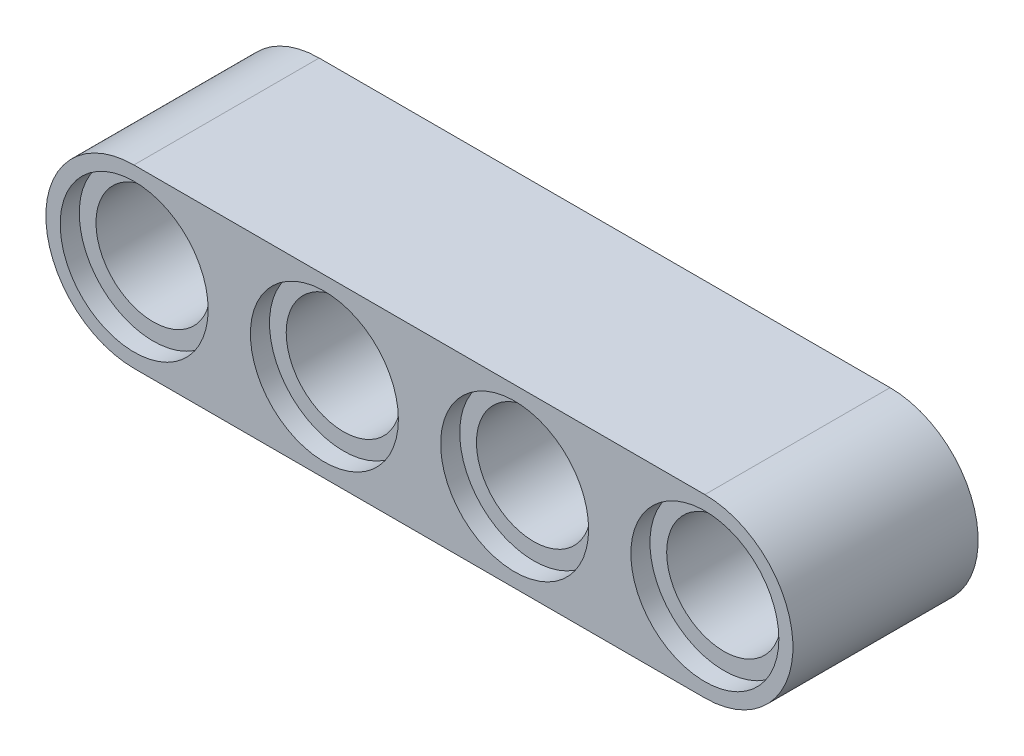
SolidWorks part; units mm, degrees
ref_plane "Front Plane" through (0, 0, 0) normal (0, 0, 1) x (1, 0, 0)
ref_plane "Top Plane" through (0, 0, 0) normal (0, 1, 0) x (1, 0, 0)
ref_plane "Right Plane" through (0, 0, 0) normal (1, 0, 0) x (0, 0, -1)
sketch "Sketch1" plane through (0, 0, 0) normal (0, 0, 1) x (1, 0, 0)
  line L0 (-88.6862, 0) -> (-64.7662, 0) construction
  line L1 (-88.6862, 3.69) -> (-64.7662, 3.69)
  line L2 (-88.6862, -3.69) -> (-64.7662, -3.69)
  arc A0 (-88.6862, 3.69) -> (-88.6862, -3.69) centre (-88.6862, 0) ccw
  arc A1 (-64.7662, -3.69) -> (-64.7662, 3.69) centre (-64.7662, 0) ccw
  point P3 (-76.7262, 0)
  dimension "D1" = 23.92
extrude "Boss-Extrude1" add sketch "Sketch1" along normal blind 7.76
sketch "Sketch2" plane through (0, 0, 0) normal (0, 0, -1) x (-1, 0, 0)
  circle A0 centre (64.7662, 0) radius 3.1
  circle A1 centre (72.7362, 0) radius 3.1
  circle A2 centre (80.7062, 0) radius 3.1
  circle A3 centre (88.6762, 0) radius 3.1
  dimension "D1" = 4
extrude "Cut-Extrude1" cut sketch "Sketch2" against normal blind 0.8
sketch "Sketch3" plane through (0, 0, 0.8) normal (0, 0, -1) x (-1, 0, 0)
  circle A0 centre (64.7662, 0) radius 2.4
  circle A1 centre (72.7362, 0) radius 2.4
  circle A2 centre (80.7062, 0) radius 2.4
  circle A3 centre (88.6762, 0) radius 2.4
  dimension "D1" = 4
extrude "Cut-Extrude2" cut sketch "Sketch3" against normal through all
sketch "Sketch4" plane through (0, 0, 7.76) normal (0, 0, 1) x (1, 0, 0)
  circle A0 centre (-88.6762, 0) radius 3.1
  circle A1 centre (-80.7062, 0) radius 3.1
  circle A2 centre (-72.7362, 0) radius 3.1
  circle A3 centre (-64.7662, 0) radius 3.1
  dimension "D1" = 4
extrude "Cut-Extrude3" cut sketch "Sketch4" against normal blind 0.8
